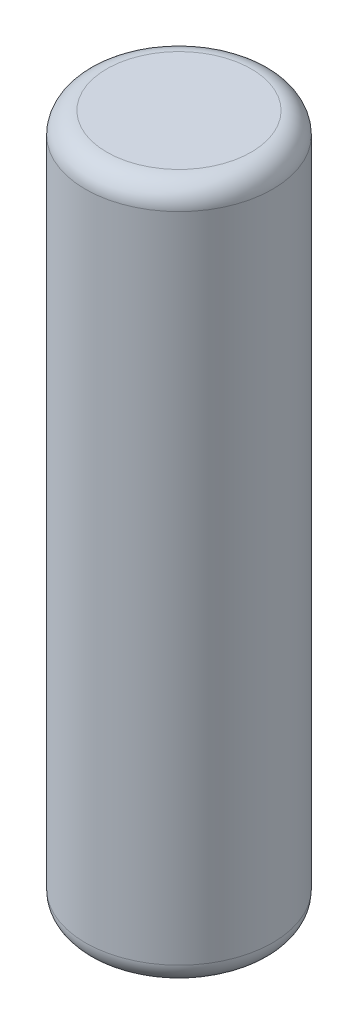
SolidWorks part; units mm, degrees
ref_plane "Front Plane" through (0, 0, 0) normal (0, 0, 1) x (1, 0, 0)
ref_plane "Top Plane" through (0, 0, 0) normal (0, 1, 0) x (1, 0, 0)
ref_plane "Right Plane" through (0, 0, 0) normal (1, 0, 0) x (0, 0, -1)
sketch "Sketch1" plane through (0, 0, 0) normal (0, 1, 0) x (1, 0, 0)
  circle A0 centre (0, 0) radius 8.89
  dimension "D1" = 17.78
extrude "Boss-Extrude1" add sketch "Sketch1" along normal blind 66.04
fillet "Fillet1" radius 2.032 2 edges at (0, 0, 8.89) (0, 66.04, 8.89)
